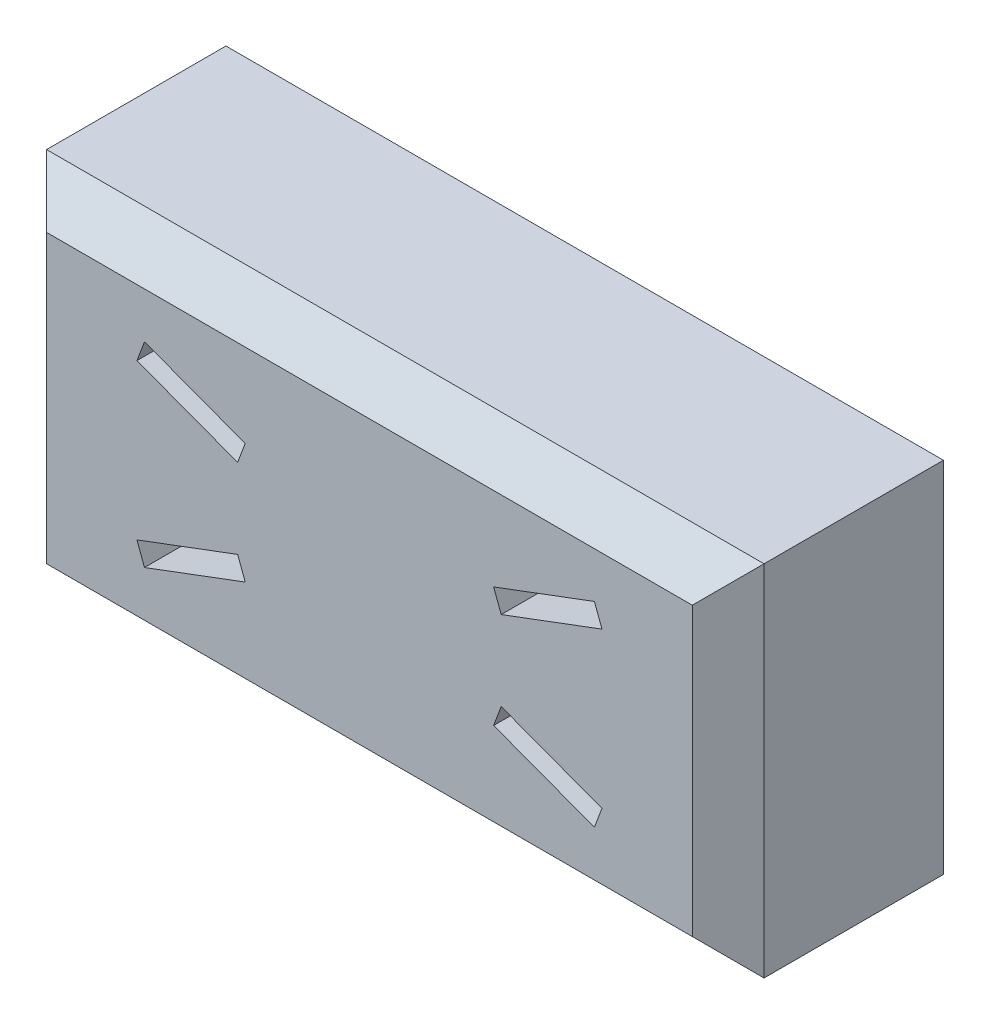
SolidWorks part; units mm, degrees
ref_plane "前视基准面" through (0, 0, 0) normal (0, 0, 1) x (1, 0, 0)
ref_plane "上视基准面" through (0, 0, 0) normal (0, 1, 0) x (1, 0, 0)
ref_plane "右视基准面" through (0, 0, 0) normal (1, 0, 0) x (0, 0, -1)
sketch "草图1" plane through (0, 0, 0) normal (0, 0, 1) x (1, 0, 0)
  line L1 (-5, -2.5) -> (5, -2.5)
  line L2 (-5, -2.5) -> (-5, 2.5)
  line L3 (-5, 2.5) -> (5, 2.5)
  line L4 (5, -2.5) -> (5, 2.5)
  line L5 (-5, -2.5) -> (5, 2.5) construction
  line L6 (-5, 2.5) -> (5, -2.5) construction
  point P0 (0, 0)
  dimension "D1" = 5
  dimension "D2" = 10
extrude "凸台-拉伸1" add sketch "草图1" along normal blind 3
chamfer "倒角1" distance 0.5 angle 45 4 edges at (0, -2.5, 3) (-5, 0, 3) (0, 2.5, 3) (5, 0, 3)
sketch "草图2" plane through (0, 0, 3) normal (0, 0, 1) x (1, 0, 0)
  line L0 (-4.5, 2) -> (4.5, -2) construction
  line L1 (4.5, 2) -> (-4.5, -2) construction
  line L2 (1.7312, 0.8362) -> (1.8365, 0.5553)
  line L7 (0, 0) -> (-7.2476, 0) construction
  line L8 (0, 0) -> (0, 2.3389) construction
  line L9 (-1.7312, 0.8362) -> (-3.1357, 1.3629)
  line L10 (-3.241, 1.082) -> (-3.1357, 1.3629)
  line L11 (-1.8365, 0.5553) -> (-3.241, 1.082)
  line L12 (-1.7312, 0.8362) -> (-1.8365, 0.5553)
  line L21 (1.8365, 0.5553) -> (3.241, 1.082)
  line L22 (3.241, 1.082) -> (3.1357, 1.3629)
  line L23 (1.7312, 0.8362) -> (3.1357, 1.3629)
  line L24 (1.7312, -0.8362) -> (3.1357, -1.3629)
  line L25 (3.241, -1.082) -> (3.1357, -1.3629)
  line L26 (1.8365, -0.5553) -> (3.241, -1.082)
  line L27 (1.7312, -0.8362) -> (1.8365, -0.5553)
  line L28 (-1.7312, -0.8362) -> (-1.8365, -0.5553)
  line L29 (-1.8365, -0.5553) -> (-3.241, -1.082)
  line L30 (-3.241, -1.082) -> (-3.1357, -1.3629)
  line L31 (-1.7312, -0.8362) -> (-3.1357, -1.3629)
  point P6 (0, 0)
  point P23 (-1.8365, 0.5553)
  point P24 (-4.4775, 1.5456)
  point P37 (0, 0)
  dimension "D2" = 1.5
  dimension "D3" = 0.3
extrude "切除-拉伸1" cut sketch "草图2" against normal blind 1
